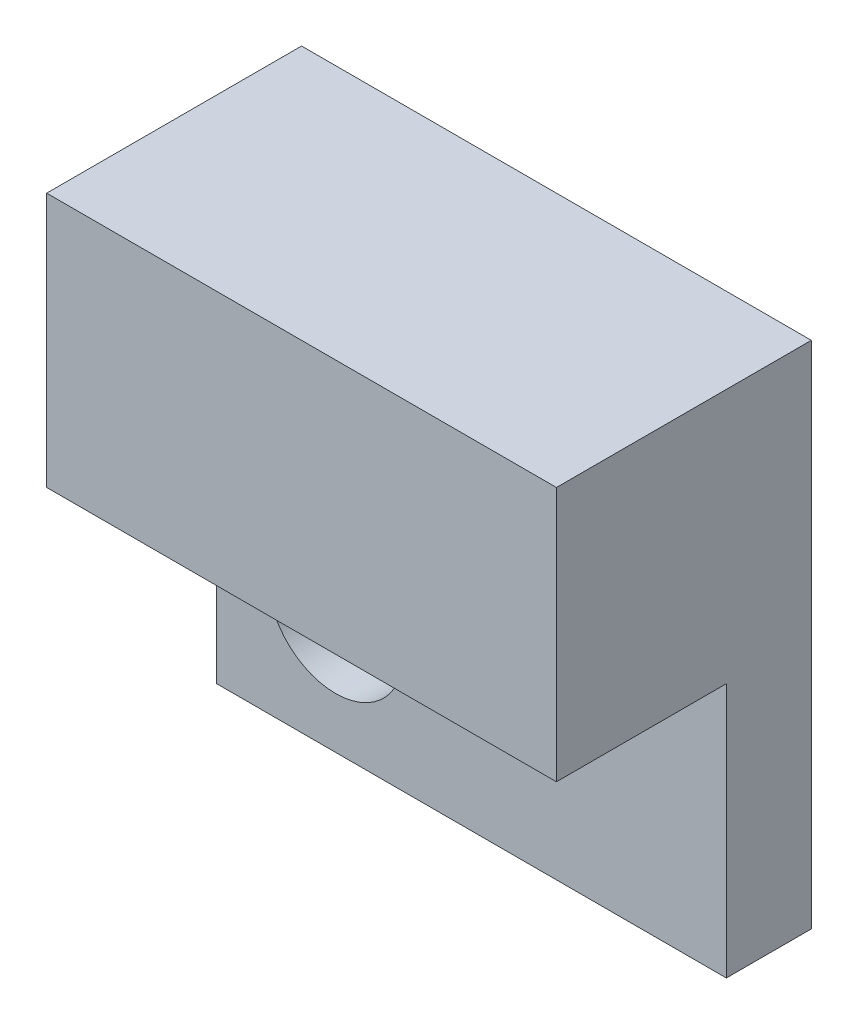
SolidWorks part; units mm, degrees
material "SKD11淬火HRC56-60"
ref_plane "前基準面" through (0, 0, 0) normal (0, 0, 1) x (1, 0, 0)
ref_plane "上基準面" through (0, 0, 0) normal (0, 1, 0) x (1, 0, 0)
ref_plane "右基準面" through (0, 0, 0) normal (1, 0, 0) x (0, 0, -1)
sketch "草图1" plane through (0, 0, 0) normal (0, 0, 1) x (1, 0, 0)
  line L1 (0, 0) -> (30, 0)
  line L2 (0, 0) -> (0, 30)
  line L3 (0, 30) -> (30, 30)
  line L4 (30, 0) -> (30, 30)
  dimension "D1" = 30
  dimension "D2" = 30
extrude "凸台-拉伸1" add sketch "草图1" along normal blind 15
sketch "草图2" plane through (0, 0, 15) normal (0, 0, 1) x (1, 0, 0)
  line L0 (0, 30) -> (0, 0) construction
  line L1 (0, 0) -> (30, 0) construction
  circle A0 centre (7, 7) radius 4
  dimension "D1" = 8
  dimension "D2" = 7
  dimension "D3" = 7
extrude "切除-拉伸1" cut sketch "草图2" against normal through all
sketch "草图3" plane through (0, 0, 0) normal (-1, 0, 0) x (0, 0, 1)
  line L0 (0, 30) -> (0, 0) construction
  line L1 (15, 0) -> (5, 0)
  line L2 (15, 0) -> (15, 15)
  line L3 (15, 15) -> (5, 15)
  line L4 (5, 0) -> (5, 15)
  dimension "D1" = 15
  dimension "D2" = 5
extrude "切除-拉伸2" cut sketch "草图3" against normal through all
